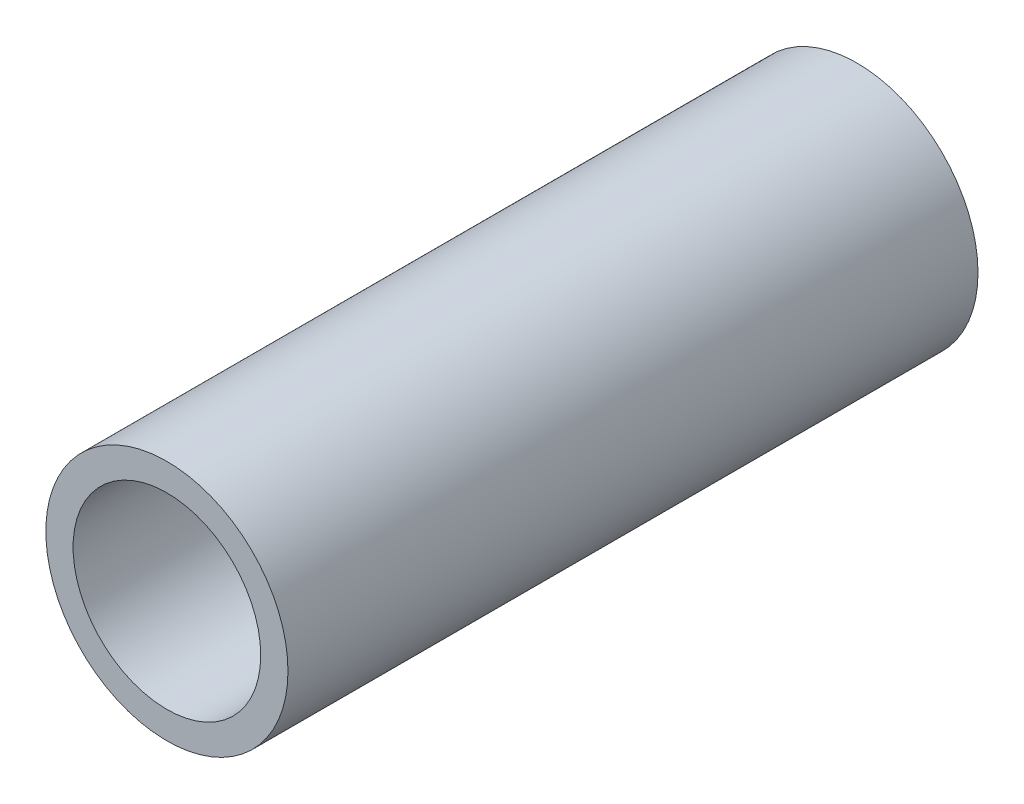
SolidWorks part; units mm, degrees
ref_plane "Спереди" through (0, 0, 0) normal (0, 0, 1) x (1, 0, 0)
ref_plane "Сверху" through (0, 0, 0) normal (0, 1, 0) x (1, 0, 0)
ref_plane "Справа" through (0, 0, 0) normal (1, 0, 0) x (0, 0, -1)
sketch "Эскиз1" plane through (0, 0, 0) normal (0, 0, 1) x (1, 0, 0)
  circle A0 centre (0, 0) radius 1
  circle A1 centre (0, 0) radius 0.775
extrude "Бобышка-Вытянуть1" add sketch "Эскиз1" along normal blind 5.7
